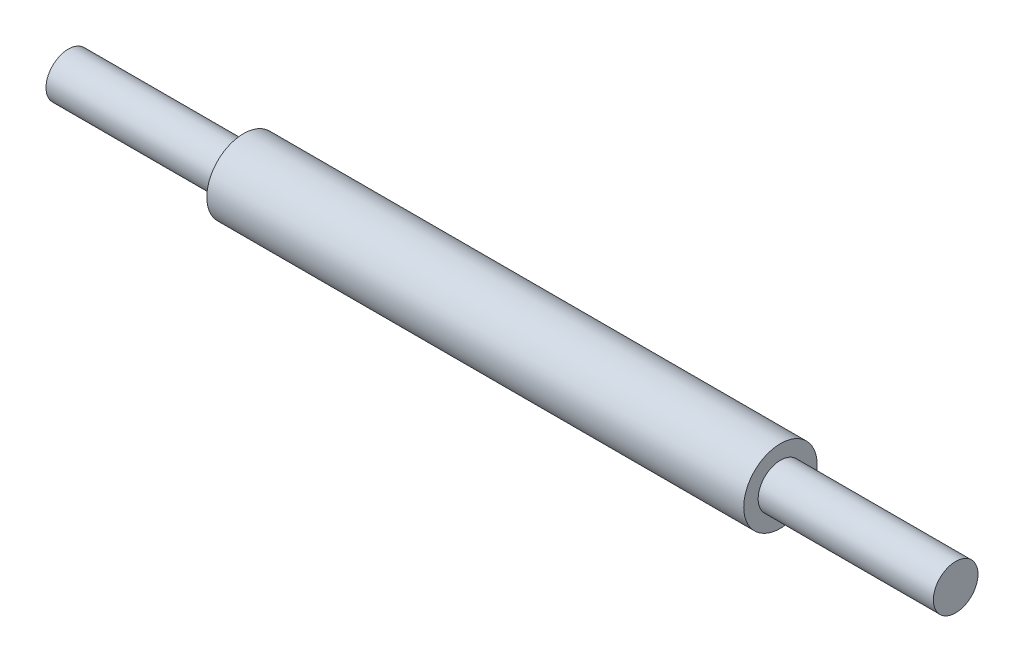
SolidWorks part; units mm, degrees
ref_plane "Front Plane" through (0, 0, 0) normal (0, 0, 1) x (1, 0, 0)
ref_plane "Top Plane" through (0, 0, 0) normal (0, 1, 0) x (1, 0, 0)
ref_plane "Right Plane" through (0, 0, 0) normal (1, 0, 0) x (0, 0, -1)
sketch "Sketch1" plane through (0, 0, 0) normal (1, 0, 0) x (0, 0, -1)
  circle A0 centre (0, 0) radius 3.95
  dimension "D1" = 7.9
extrude "Boss-Extrude1" add sketch "Sketch1" along normal blind 31
sketch "Sketch2" plane through (0, 0, 0) normal (-1, 0, 0) x (0, 0, 1)
  circle A0 centre (0, 0) radius 6.5
  dimension "D1" = 13
extrude "Boss-Extrude2" add sketch "Sketch2" along normal blind 95
sketch "Sketch3" plane through (-95, 0, 0) normal (-1, 0, 0) x (0, 0, 1)
  circle A0 centre (0, 0) radius 3.95
  dimension "D1" = 7.9
extrude "Boss-Extrude3" add sketch "Sketch3" along normal blind 31
